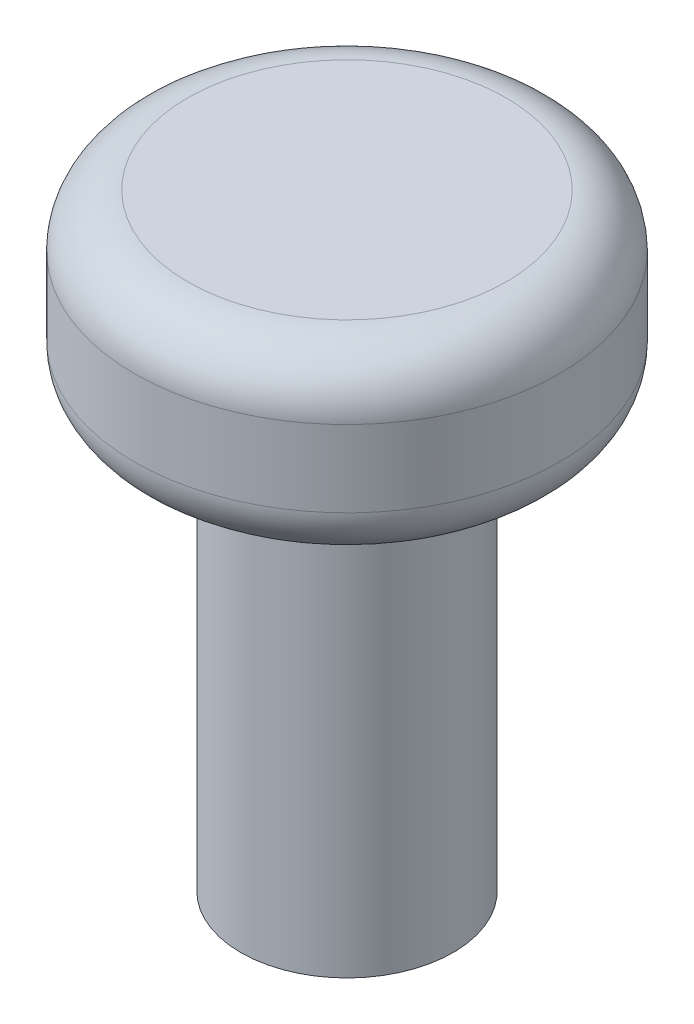
SolidWorks part; units mm, degrees
material "EN8"
ref_plane "Front Plane" through (0, 0, 0) normal (0, 0, 1) x (1, 0, 0)
ref_plane "Top Plane" through (0, 0, 0) normal (0, 1, 0) x (1, 0, 0)
ref_plane "Right Plane" through (0, 0, 0) normal (1, 0, 0) x (0, 0, -1)
sketch "Sketch1" plane through (0, 0, 0) normal (0, 0, 1) x (1, 0, 0)
  line L0 (0, 0) -> (-1, 0)
  line L1 (-1, 0) -> (-1, 4)
  line L2 (-1, 4) -> (-2, 4)
  line L3 (-2, 4) -> (-2, 5.72)
  line L4 (-2, 5.72) -> (0, 5.72)
  line L5 (0, 5.72) -> (0, 0)
  point P7 (-2, 4.0571)
  dimension "D1" = 1
  dimension "D2" = 2
  dimension "D3" = 1.72
  dimension "D4" = 4
revolve "Revolve1" add sketch "Sketch1" angle 360 about L5
fillet "Fillet1" radius 0.5 2 edges at (0, 4, 2) (0, 5.72, 2)
